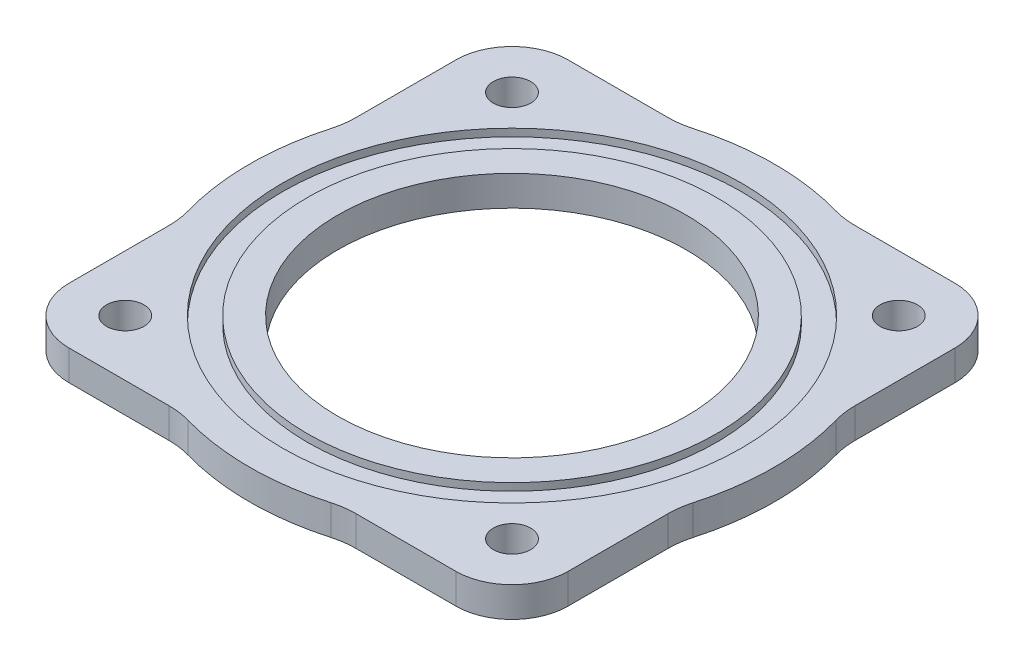
SolidWorks part; units mm, degrees
ref_plane "Front Plane" through (0, 0, 0) normal (0, 0, 1) x (1, 0, 0)
ref_plane "Top Plane" through (0, 0, 0) normal (0, 1, 0) x (1, 0, 0)
ref_plane "Right Plane" through (0, 0, 0) normal (1, 0, 0) x (0, 0, -1)
sketch "Sketch1" plane through (0, 0, 0) normal (0, 1, 0) x (1, 0, 0)
  line L0 (0, 43.6291) -> (0, 56.3563)
  line L1 (7.1437, 0) -> (19.8709, 0)
  line L2 (0, 7.1437) -> (0, 19.8709)
  line L3 (7.1437, 63.5) -> (19.8709, 63.5)
  line L4 (63.5, 7.1437) -> (63.5, 19.8709)
  line L5 (43.6291, 63.5) -> (56.3563, 63.5)
  line L6 (63.5, 43.6291) -> (63.5, 56.3563)
  line L7 (43.6291, 0) -> (56.3563, 0)
  circle A0 centre (31.75, 31.75) radius 22.1742
  circle A1 centre (56.3563, 56.3563) radius 2.3812
  circle A2 centre (56.3563, 7.1437) radius 2.3812
  circle A3 centre (7.1437, 7.1437) radius 2.3812
  circle A4 centre (7.1437, 56.3563) radius 2.3812
  arc A7 (7.1437, 63.5) -> (0, 56.3563) centre (7.1437, 56.3563) ccw
  arc A8 (56.3563, 0) -> (63.5, 7.1437) centre (56.3563, 7.1437) ccw
  arc A9 (0, 7.1437) -> (7.1437, 0) centre (7.1437, 7.1437) ccw
  arc A10 (63.5, 56.3563) -> (56.3563, 63.5) centre (56.3563, 56.3563) ccw
  arc A11 (-0.3851, 40.8585) -> (-0.3851, 22.6415) centre (31.75, 31.75) ccw
  arc A12 (22.6415, -0.3851) -> (40.8585, -0.3851) centre (31.75, 31.75) ccw
  arc A13 (40.8585, 63.8851) -> (22.6415, 63.8851) centre (31.75, 31.75) ccw
  arc A14 (63.8851, 22.6415) -> (63.8851, 40.8585) centre (31.75, 31.75) ccw
  arc A15 (63.8851, 40.8585) -> (63.5, 43.6291) centre (73.66, 43.6291) cw
  arc A16 (63.5, 19.8709) -> (63.8851, 22.6415) centre (73.66, 19.8709) cw
  arc A17 (40.8585, -0.3851) -> (43.6291, 0) centre (43.6291, -10.16) cw
  arc A18 (22.6415, -0.3851) -> (19.8709, 0) centre (19.8709, -10.16) ccw
  arc A19 (0, 19.8709) -> (-0.3851, 22.6415) centre (-10.16, 19.8709) ccw
  arc A20 (-0.3851, 40.8585) -> (0, 43.6291) centre (-10.16, 43.6291) ccw
  arc A21 (22.6415, 63.8851) -> (19.8709, 63.5) centre (19.8709, 73.66) cw
  arc A22 (43.6291, 63.5) -> (40.8585, 63.8851) centre (43.6291, 73.66) cw
  point P16 (63.5, 42.1213)
  point P31 (63.5, 21.3787)
  point P34 (42.1213, 0)
  point P41 (0, 42.1213)
  point P46 (42.1213, 63.5)
  dimension "D3" = 44.3484
  dimension "D6" = 4.7625
  dimension "D7" = 4.7625
  dimension "D8" = 4.7625
  dimension "D9" = 4.7625
  dimension "D10" = 7.1437
  dimension "D11" = 7.1437
  dimension "D12" = 7.1437
  dimension "D13" = 7.1437
  dimension "D14" = 7.1437
  dimension "D15" = 7.1437
  dimension "D16" = 7.1437
  dimension "D17" = 7.1437
  dimension "D18" = 49.2125
  dimension "D2" = 10.16
  dimension "D19" = 11.2268
  dimension "D4" = 31.75
  dimension "D5" = 31.75
extrude "Boss-Extrude1" add sketch "Sketch1" against normal blind 3.8354
sketch "Sketch2" plane through (0, 0, 0) normal (0, 1, 0) x (1, 0, 0)
  circle A0 centre (31.75, 31.75) radius 26.035
  circle A1 centre (31.75, 31.75) radius 29.21
  dimension "D1" = 52.07
  dimension "D2" = 58.42
extrude "Cut-Extrude1" cut sketch "Sketch2" against normal blind 0.9525
